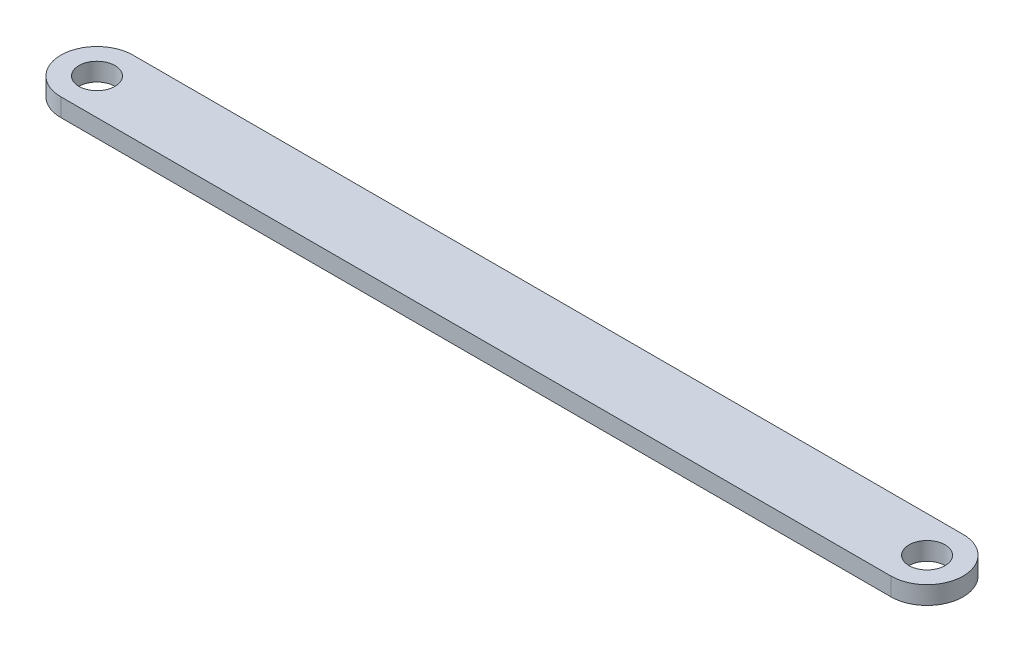
SolidWorks part; units mm, degrees
ref_plane "Front Plane" through (0, 0, 0) normal (0, 0, 1) x (1, 0, 0)
ref_plane "Top Plane" through (0, 0, 0) normal (0, 1, 0) x (1, 0, 0)
ref_plane "Right Plane" through (0, 0, 0) normal (1, 0, 0) x (0, 0, -1)
sketch "Sketch1" plane through (0, 0, 0) normal (0, 1, 0) x (1, 0, 0)
  line L0 (-72.3468, 0) -> (157.6532, 0) construction
  line L1 (-72.3468, 10) -> (157.6532, 10)
  line L2 (-72.3468, -10) -> (157.6532, -10)
  arc A0 (-72.3468, 10) -> (-72.3468, -10) centre (-72.3468, 0) ccw
  arc A1 (157.6532, -10) -> (157.6532, 10) centre (157.6532, 0) ccw
  circle A2 centre (-72.3468, 0) radius 5
  circle A3 centre (157.6532, 0) radius 5
  point P3 (42.6532, 0)
  dimension "D1" = 230
  dimension "D2" = 10
  dimension "D3" = 10
  dimension "D4" = 10
extrude "Boss-Extrude1" add sketch "Sketch1" along normal blind 5
